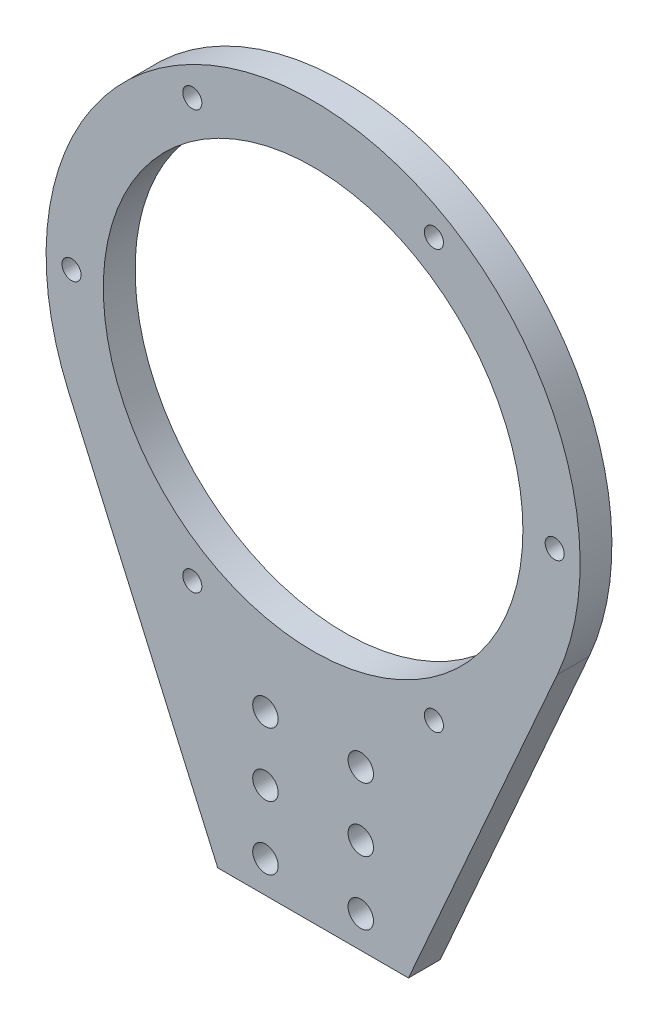
SolidWorks part; units mm, degrees
material "Acrylic (Medium-high impact)"
ref_plane "Front Plane" through (0, 0, 0) normal (0, 0, 1) x (1, 0, 0)
ref_plane "Top Plane" through (0, 0, 0) normal (0, 1, 0) x (1, 0, 0)
ref_plane "Right Plane" through (0, 0, 0) normal (1, 0, 0) x (0, 0, -1)
sketch "Sketch1" plane through (0, 0, 0) normal (0, 0, 1) x (1, 0, 0)
  line L0 (0, 0) -> (0, -75.7544) construction
  line L1 (-15, -70) -> (15, -70)
  line L4 (15, -70) -> (38.4203, -16.9671)
  line L5 (-15, -70) -> (-38.4203, -16.9671)
  line L6 (-38.4203, -16.9671) -> (0, 0) construction
  line L7 (0, 0) -> (38.4203, -16.9671) construction
  circle A0 centre (0, 0) radius 33
  circle A1 centre (0, 0) radius 42
  arc A2 (-38.4203, -16.9671) -> (38.4203, -16.9671) centre (0, 0) ccw
  dimension "D1" = 30
  dimension "D2" = 84
  dimension "D3" = 66
  dimension "D4" = 70
  dimension "D6" = 15
extrude "Boss-Extrude1" add sketch "Sketch1" along normal blind 5
sketch "Sketch9" plane through (0, 0, 5) normal (0, 0, 1) x (1, 0, 0)
  line L0 (60.1553, 0) -> (-60.1553, 0) construction
  line L1 (-60.1553, 0) -> (0, 0) construction
  line L2 (0, 0) -> (27.4803, 47.5973) construction
  line L3 (27.4803, 47.5973) -> (-28.626, -49.5817) construction
  line L4 (-28.626, -49.5817) -> (0, 0) construction
  line L5 (-29.2217, 50.6135) -> (0, 0) construction
  line L6 (0, 0) -> (29.2328, -50.6327) construction
  circle A0 centre (0, 0) radius 38 construction
  circle A1 centre (19, 32.909) radius 1.5
  circle A2 centre (38, 0) radius 1.5
  circle A3 centre (19, -32.909) radius 1.5
  circle A4 centre (-19, -32.909) radius 1.5
  circle A5 centre (-38, 0) radius 1.5
  circle A6 centre (-19, 32.909) radius 1.5
  dimension "D1" = 60
  dimension "D2" = 60
extrude "Cut-Extrude5" cut sketch "Sketch9" against normal blind 7
sketch "Sketch10" plane through (0, 0, 5) normal (0, 0, 1) x (1, 0, 0)
  line L0 (0, 0) -> (0, -98.5039) construction
  line L2 (-15, -70) -> (15, -70) construction
  circle A1 centre (7.5, -55) radius 2
  circle A2 centre (7.5, -65) radius 2
  circle A3 centre (-7.5, -65) radius 2
  circle A4 centre (-7.5, -55) radius 2
  circle A6 centre (0, 0) radius 37.5 construction
  circle A7 centre (-7.5, -45) radius 2
  circle A8 centre (7.5, -45) radius 2
  dimension "D2" = 10
  dimension "D3" = 7.5
  dimension "D4" = 7.5
  dimension "D5" = 7.5
  dimension "D6" = 7.5
  dimension "D7" = 5
  dimension "D8" = 10
  dimension "D9" = 10
  dimension "D10" = 5
  dimension "D11" = 10
extrude "Cut-Extrude6" cut sketch "Sketch10" against normal blind 7
